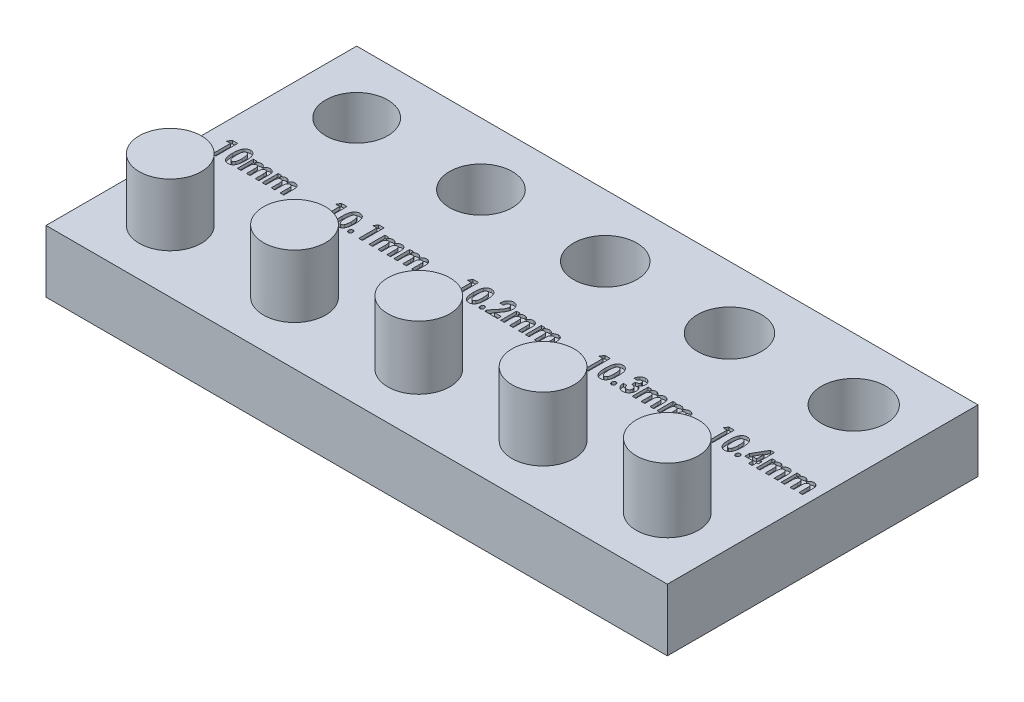
SolidWorks part; units mm, degrees
ref_plane "Front Plane" through (0, 0, 0) normal (0, 0, 1) x (1, 0, 0)
ref_plane "Top Plane" through (0, 0, 0) normal (0, 1, 0) x (1, 0, 0)
ref_plane "Right Plane" through (0, 0, 0) normal (1, 0, 0) x (0, 0, -1)
sketch "Sketch1" plane through (0, 0, 0) normal (0, 1, 0) x (1, 0, 0)
  line L1 (0, 0) -> (100, 0)
  line L2 (0, 0) -> (0, 50)
  line L3 (0, 50) -> (100, 50)
  line L4 (100, 0) -> (100, 50)
extrude "Boss-Extrude1" add sketch "Sketch1" along normal blind 10
sketch "Sketch2" plane through (0, 10, 0) normal (0, 1, 0) x (1, 0, 0)
  line L0 (0, 50) -> (0, 0) construction
  line L1 (0, 0) -> (100, 0) construction
  circle A0 centre (10, 10) radius 5
  point P2 (0, 0)
extrude "Boss-Extrude2" add sketch "Sketch2" along normal blind 10 contours A0
sketch "Sketch4" plane through (0, 10, 0) normal (0, 1, 0) x (1, 0, 0)
  line L0 (10, 10) -> (100, 10) construction
  line L1 (100, 0) -> (100, 50) construction
  circle A0 centre (30, 10) radius 5
extrude "Boss-Extrude3" add sketch "Sketch4" along normal blind 10.1 contours A0
sketch "Sketch5" plane through (0, 10, 0) normal (0, 1, 0) x (1, 0, 0)
  line L0 (10, 10) -> (100, 10) construction
  line L1 (100, 0) -> (100, 50) construction
  circle A0 centre (50, 10) radius 5
  circle A1 centre (30, 10) radius 5 construction
extrude "Boss-Extrude4" add sketch "Sketch5" along normal blind 10.2 contours A0
sketch "Sketch6" plane through (0, 10, 0) normal (0, 1, 0) x (1, 0, 0)
  line L0 (50, 10) -> (100, 10) construction
  line L1 (100, 0) -> (100, 50) construction
  circle A0 centre (70, 10) radius 5
extrude "Boss-Extrude5" add sketch "Sketch6" along normal blind 10.3 contours A0
sketch "Sketch7" plane through (0, 10, 0) normal (0, 1, 0) x (1, 0, 0)
  line L0 (70, 10) -> (100, 10) construction
  line L1 (100, 0) -> (100, 50) construction
  circle A0 centre (90, 10) radius 5
extrude "Boss-Extrude6" add sketch "Sketch7" along normal blind 10.4 contours A0
sketch "Sketch8" plane through (0, 10, 0) normal (0, 1, 0) x (1, 0, 0)
  line L0 (10, 10) -> (10, 50) construction
  line L1 (100, 50) -> (0, 50) construction
  line L2 (10, 40) -> (100, 40) construction
  line L3 (100, 0) -> (100, 50) construction
  line L5 (30, 10) -> (30, 50) construction
  line L6 (50, 10) -> (50, 50) construction
  line L7 (70, 10) -> (70, 50) construction
  line L8 (90, 10) -> (90, 50) construction
  circle A0 centre (10, 40) radius 5
  circle A1 centre (30, 40) radius 5.05
  circle A2 centre (50, 40) radius 5.1
  circle A3 centre (70, 40) radius 5.15
  circle A4 centre (90, 40) radius 5.2
extrude "Cut-Extrude1" cut sketch "Sketch8" against normal through all contours A0 | A1 | A2 | A3 | A4
sketch "Sketch10" plane through (0, 10, 0) normal (0, 1, 0) x (1, 0, 0)
  line L0 (0, 23.3635) -> (100, 23.3635) construction
  line L1 (0, 50) -> (0, 0) construction
  line L2 (100, 0) -> (100, 50) construction
  text T0 "<b>  10mm    10.1mm    10.2mm    10.3mm   10.4mm</b>\r\n" font "Century Gothic" height 3.5
extrude "Cut-Extrude2" cut sketch "Sketch10" against normal blind 0.5
equation "\"b\"= 50'base [mm]"
equation "\"h\"= 10'height [mm]"
equation "\"l\"= 100'length [mm]"
equation "\"T1\"= 10'Test 1 [mm]"
equation "\"T2\"= 10.1'Test 2 [mm]"
equation "\"T3\"= 10.2'Test 3 [mm]"
equation "\"T4\"= 10.3'Test 4 [mm]"
equation "\"T5\"= 10.4'Test 5 [mm]"
equation "\"D1@Sketch1\"=\"b\""
equation "\"D2@Sketch1\"=\"l\""
equation "\"D1@Boss-Extrude1\"=\"h\""
equation "\"D1@Sketch2\"=\"T1\""
equation "\"D1@Boss-Extrude2\"=\"T1\""
equation "\"D1@Sketch4\"=\"T1\""
equation "\"D1@Boss-Extrude3\"=\"T2\""
equation "\"D1@Sketch5\"=\"T1\""
equation "\"D1@Boss-Extrude4\"=\"T3\""
equation "\"D1@Sketch6\"=\"T1\""
equation "\"D1@Boss-Extrude5\"=\"T4\""
equation "\"D1@Sketch7\"=\"T1\""
equation "\"D1@Boss-Extrude6\"=\"T5\""
equation "\"D2@Sketch8\"=\"T1\""
equation "\"D3@Sketch8\"=\"T2\""
equation "\"D4@Sketch8\"=\"T3\""
equation "\"D5@Sketch8\"=\"T4\""
